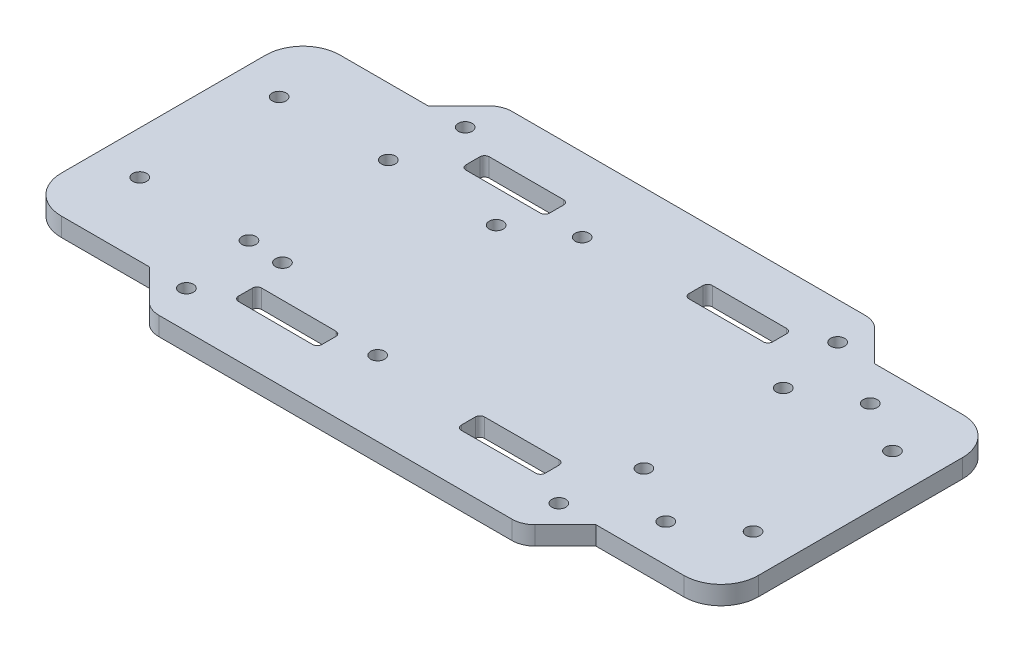
SolidWorks part; units mm, degrees
ref_plane "Front Plane" through (0, 0, 0) normal (0, 0, 1) x (1, 0, 0)
ref_plane "Top Plane" through (0, 0, 0) normal (0, 1, 0) x (1, 0, 0)
ref_plane "Right Plane" through (0, 0, 0) normal (1, 0, 0) x (0, 0, -1)
sketch "Sketch1" plane through (0, 0, 0) normal (0, 1, 0) x (1, 0, 0)
  line L0 (-48.3172, 29.9016) -> (-41.7816, 36.4371)
  line L1 (-67.2461, -30.0984) -> (-48.3172, -30.0984)
  line L2 (-75.2461, -22.0984) -> (-75.2461, 21.9016)
  line L3 (-67.2461, 29.9016) -> (-48.3172, 29.9016)
  line L4 (74.7539, -22.0984) -> (74.7539, 21.9016)
  line L6 (-71.7594, -28.7038) -> (71.2672, 28.5069) construction
  line L7 (47.825, 29.9016) -> (66.7539, 29.9016)
  line L9 (-71.7594, 28.5069) -> (71.2672, -28.7038) construction
  line L10 (37.7539, 37.9016) -> (-38.2461, 37.9016)
  line L12 (47.825, 29.9016) -> (41.2894, 36.4371)
  line L13 (47.825, -30.0984) -> (41.2894, -36.634)
  line L14 (-48.3172, -30.0984) -> (-41.7816, -36.634)
  line L15 (37.7539, -38.0984) -> (-38.2461, -38.0984)
  line L16 (47.825, -30.0984) -> (66.7539, -30.0984)
  line L28 (-15, -6) -> (15, 6) construction
  arc A4 (-75.2461, 21.9016) -> (-67.2461, 29.9016) centre (-67.2461, 21.9016) cw
  arc A5 (-67.2461, -30.0984) -> (-75.2461, -22.0984) centre (-67.2461, -22.0984) cw
  arc A6 (74.7539, 21.9016) -> (66.7539, 29.9016) centre (66.7539, 21.9016) ccw
  arc A7 (74.7539, -22.0984) -> (66.7539, -30.0984) centre (66.7539, -22.0984) cw
  arc A8 (-41.7816, 36.4371) -> (-38.2461, 37.9016) centre (-38.2461, 32.9016) cw
  arc A9 (41.2894, 36.4371) -> (37.7539, 37.9016) centre (37.7539, 32.9016) ccw
  arc A10 (-38.2461, -38.0984) -> (-41.7816, -36.634) centre (-38.2461, -33.0984) cw
  arc A11 (37.7539, -38.0984) -> (41.2894, -36.634) centre (37.7539, -33.0984) ccw
  circle A16 centre (-7.2461, 22) radius 1.5
  circle A17 centre (54.7539, 22) radius 1.5
  circle A18 centre (54.7539, -22) radius 1.5
  circle A19 centre (-7.2461, -22) radius 1.5
  point P0 (0, 0)
  point P20 (0, 0)
  point P23 (0, 0)
  point P48 (0, 0)
  dimension "D3" = 60
  dimension "D4" = 8
  dimension "D5" = 8
  dimension "D6" = 8
  dimension "D1" = 8
  dimension "D8" = 5
  dimension "D9" = 5
  dimension "D10" = 5
  dimension "D11" = 5
  dimension "D12" = 3
  dimension "D13" = 3
  dimension "D14" = 3
  dimension "D15" = 3
  dimension "D18" = 62
  dimension "D17" = 62
  dimension "D19" = 20
  dimension "D21" = 20
  dimension "D2" = 150
  dimension "D7" = 76
extrude "Boss-Extrude1" add sketch "Sketch1" against normal blind 4
sketch "Sketch2" plane through (0, 0, 0) normal (0, 1, 0) x (1, 0, 0)
  circle A0 centre (-42.5, 15.5391) radius 1.5
  circle A1 centre (-66, 15.5391) radius 1.5
  circle A2 centre (-66, -14.4609) radius 1.5
  circle A3 centre (-42.5, -14.4609) radius 1.5
  circle A12 centre (66, 15.5391) radius 1.5
  circle A13 centre (66, -14.4609) radius 1.5
  circle A14 centre (42.5, -14.4609) radius 1.5
  circle A19 centre (42.5, 15.5391) radius 1.5
extrude "Cut-Extrude1" cut sketch "Sketch2" against normal blind 4
sketch "Sketch8" plane through (0, -4, 0) normal (0, -1, 0) x (1, 0, 0)
  line L3 (-38.2461, 38.0984) -> (37.7539, 38.0984) construction
  line L4 (37.7539, -37.9016) -> (-38.2461, -37.9016) construction
  circle A0 centre (-40.3172, -29.9016) radius 1.5
  circle A2 centre (39.825, -29.9016) radius 1.5
  circle A3 centre (39.825, 30.0984) radius 1.5
  circle A4 centre (-40.3172, 30.0984) radius 1.5
  dimension "D2" = 3
  dimension "D1" = 8
  dimension "D4" = 8
  dimension "D5" = 8
  dimension "D6" = 8
  dimension "D7" = 8
  dimension "D8" = 8
  dimension "D9" = 8
  dimension "D3" = 8
extrude "Cut-Extrude5" cut sketch "Sketch8" against normal through all
sketch "Sketch9" plane through (0, 0, 0) normal (0, 1, 0) x (1, 0, 0)
  circle A0 centre (-34.7478, -15) radius 1.5
  circle A1 centre (-18.7478, 15) radius 1.5
  point P0 (-26.7478, 0)
extrude "Cut-Extrude6" cut sketch "Sketch9" against normal blind 10
sketch "Sketch10" plane through (0, 0, 0) normal (0, 1, 0) x (1, 0, 0)
  line L4 (-75.2461, 21.9016) -> (-75.2461, -22.0984) construction
  line L5 (15.7539, 22) -> (31.7539, 22)
  line L6 (14.7539, 23) -> (14.7539, 26)
  line L7 (15.7539, 27) -> (31.7539, 27)
  line L8 (32.7539, 23) -> (32.7539, 26)
  line L9 (14.7539, 22) -> (32.7539, 27) construction
  line L10 (14.7539, 27) -> (32.7539, 22) construction
  line L13 (-32.2566, -26.9629) -> (-16.2567, -27.005)
  line L14 (-15.2462, -23.0077) -> (-15.2541, -26.0077)
  line L15 (-32.2435, -21.9629) -> (-16.2435, -22.005)
  line L16 (-33.2461, -22.9603) -> (-33.254, -25.9602)
  line L17 (74.7539, -22.0984) -> (74.7539, 21.9016) construction
  line L21 (32.7539, -22.9603) -> (32.7618, -25.9602)
  line L22 (31.7513, -21.9629) -> (15.7513, -22.005)
  line L23 (14.754, -23.0077) -> (14.7619, -26.0077)
  line L24 (31.7644, -26.9629) -> (15.7645, -27.005)
  line L25 (-16.2461, 27) -> (-32.2461, 27)
  line L26 (-33.2461, 23) -> (-33.2461, 26)
  line L27 (-16.2461, 22) -> (-32.2461, 22)
  line L28 (-15.2461, 23) -> (-15.2461, 26)
  arc A4 (31.7539, 27) -> (32.7539, 26) centre (31.7539, 26) cw
  arc A5 (32.7539, 23) -> (31.7539, 22) centre (31.7539, 23) cw
  arc A6 (14.7539, 23) -> (15.7539, 22) centre (15.7539, 23) ccw
  arc A7 (15.7539, 27) -> (14.7539, 26) centre (15.7539, 26) ccw
  arc A8 (-16.2567, -27.005) -> (-15.2541, -26.0077) centre (-16.2541, -26.005) ccw
  arc A9 (-15.2462, -23.0077) -> (-16.2435, -22.005) centre (-16.2462, -23.005) ccw
  arc A10 (-33.2461, -22.9603) -> (-32.2435, -21.9629) centre (-32.2461, -22.9629) cw
  arc A11 (-32.2566, -26.9629) -> (-33.254, -25.9602) centre (-32.254, -25.9629) cw
  arc A12 (31.7644, -26.9629) -> (32.7618, -25.9602) centre (31.7618, -25.9629) ccw
  arc A13 (32.7539, -22.9603) -> (31.7513, -21.9629) centre (31.7539, -22.9629) ccw
  arc A14 (14.754, -23.0077) -> (15.7513, -22.005) centre (15.754, -23.005) cw
  arc A15 (15.7645, -27.005) -> (14.7619, -26.0077) centre (15.7619, -26.005) cw
  arc A16 (-32.2461, 27) -> (-33.2461, 26) centre (-32.2461, 26) ccw
  arc A17 (-33.2461, 23) -> (-32.2461, 22) centre (-32.2461, 23) ccw
  arc A18 (-15.2461, 23) -> (-16.2461, 22) centre (-16.2461, 23) cw
  arc A19 (-16.2461, 27) -> (-15.2461, 26) centre (-16.2461, 26) cw
  point P0 (23.7539, 24.5)
  dimension "D3" = 1
  dimension "D1" = 18
  dimension "D2" = 5
  dimension "D4" = 5
  dimension "D5" = 18
  dimension "D6" = 42
  dimension "D7" = 42
extrude "Cut-Extrude7" cut sketch "Sketch10" against normal blind 10
